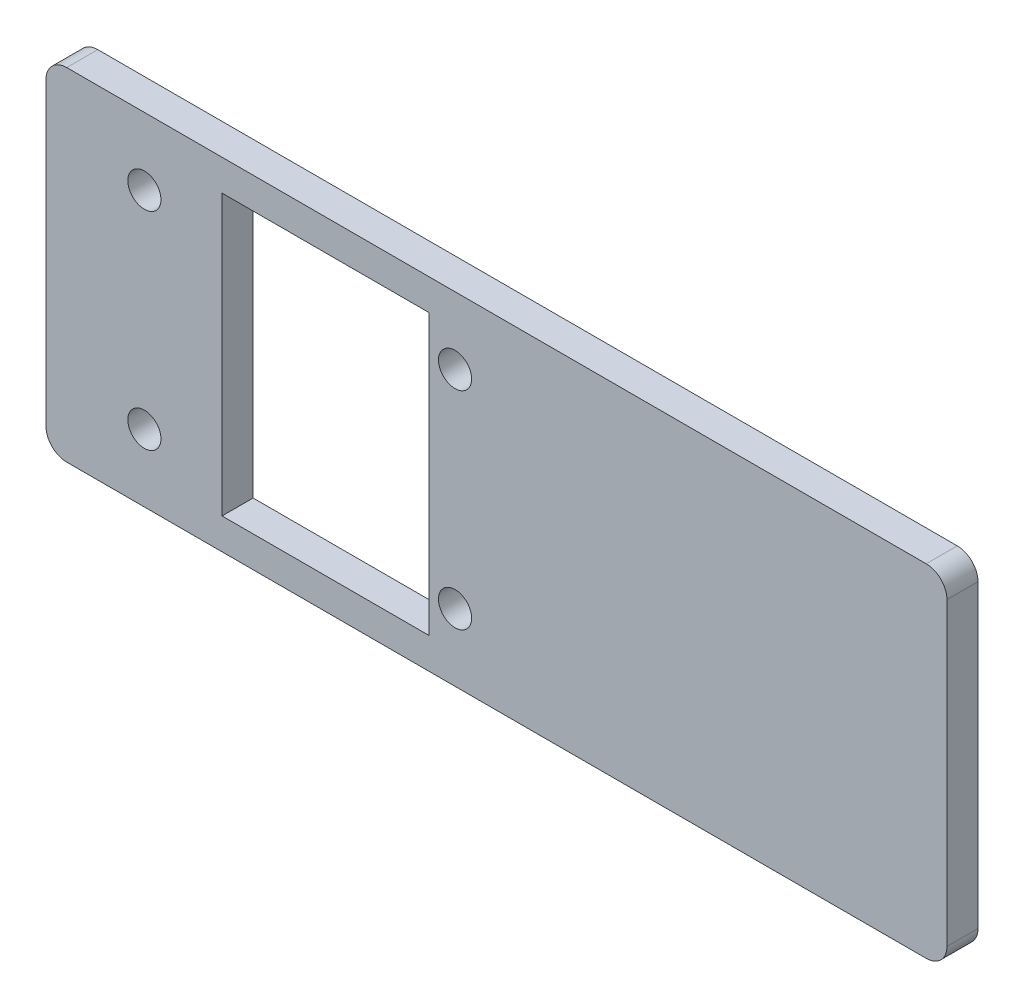
SolidWorks part; units mm, degrees
ref_plane "Front" through (0, 0, 0) normal (0, 0, 1) x (1, 0, 0)
ref_plane "Top" through (0, 0, 0) normal (0, 1, 0) x (1, 0, 0)
ref_plane "Right" through (0, 0, 0) normal (1, 0, 0) x (0, 0, -1)
sketch "Sketch1" plane through (0, 0, 0) normal (0, 0, 1) x (1, 0, 0)
  line L1 (-19.1679, 16.2582) -> (67.8321, 16.2582)
  line L2 (-19.1679, 16.2582) -> (-19.1679, -16.7418)
  line L3 (-19.1679, -16.7418) -> (67.8321, -16.7418)
  line L4 (67.8321, 16.2582) -> (67.8321, -16.7418)
  circle A0 centre (-9.6679, 9.7582) radius 1.6
  circle A1 centre (20.3321, 9.7582) radius 1.6
  circle A2 centre (-9.6679, -10.2418) radius 1.6
  circle A3 centre (20.3321, -10.2418) radius 1.6
  dimension "D7" = 3.2
  dimension "D8" = 3.2
  dimension "D9" = 3.2
  dimension "D10" = 3.2
  dimension "D1" = 87
  dimension "D2" = 33
extrude "Boss-Extrude2" add sketch "Sketch1" along normal blind 3
fillet "Fillet1" radius 2 4 edges at (-19.1679, -16.7418, 1.5) (67.8321, -16.7418, 1.5) (67.8321, 16.2582, 1.5) (-19.1679, 16.2582, 1.5)
sketch "Sketch2" plane through (0, 0, 3) normal (0, 0, 1) x (1, 0, 0)
  line L0 (-17.1679, -16.7418) -> (65.8321, -16.7418) construction
  line L1 (17.8321, 13.2582) -> (-2.1679, 13.2582)
  line L2 (17.8321, 13.2582) -> (17.8321, -13.7418)
  line L3 (17.8321, -13.7418) -> (-2.1679, -13.7418)
  line L4 (-2.1679, 13.2582) -> (-2.1679, -13.7418)
  line L5 (65.8321, 16.2582) -> (-17.1679, 16.2582) construction
  line L6 (67.8321, -14.7418) -> (67.8321, 14.2582) construction
  dimension "D1" = 20
  dimension "D2" = 3
  dimension "D3" = 3
  dimension "D4" = 50
extrude "Cut-Extrude1" cut sketch "Sketch2" against normal blind 10 contours L2 L1 L4 L3
